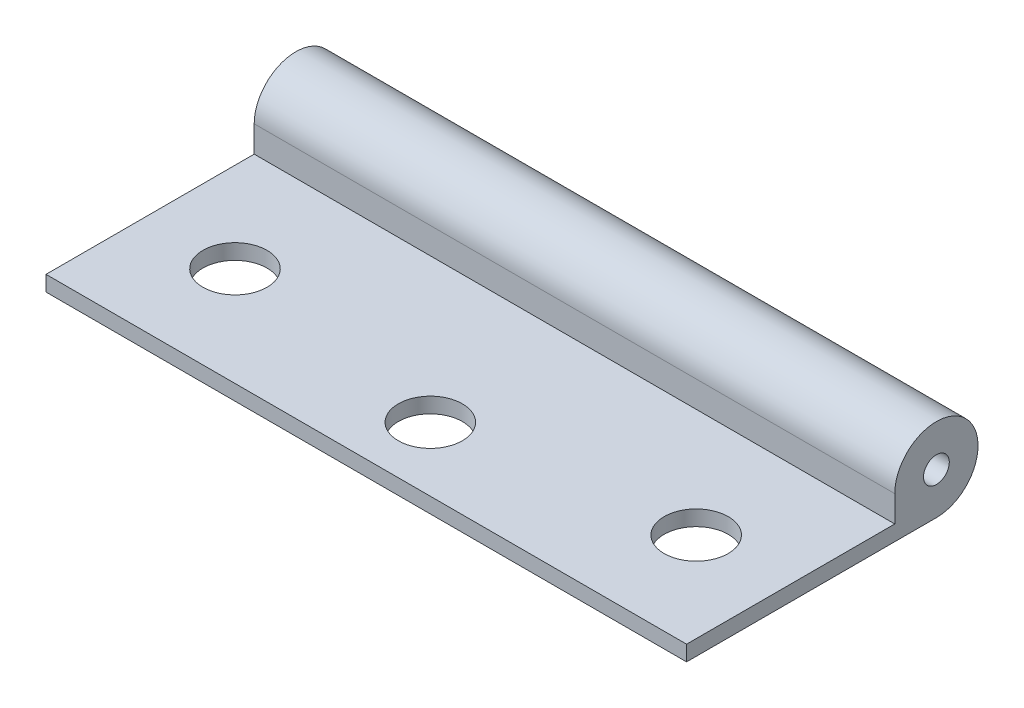
SolidWorks part; units mm, degrees
material "不锈钢 (铁素体)"
ref_plane "前视基准面" through (0, 0, 0) normal (0, 0, 1) x (1, 0, 0)
ref_plane "上视基准面" through (0, 0, 0) normal (0, 1, 0) x (1, 0, 0)
ref_plane "右视基准面" through (0, 0, 0) normal (1, 0, 0) x (0, 0, -1)
sketch "草图1" plane through (0, 0, 0) normal (0, 1, 0) x (1, 0, 0)
  line L0 (25, 0) -> (25, -16.25) construction
  line L1 (0, 0) -> (50, 0)
  line L2 (0, 0) -> (0, -16.25)
  line L3 (0, -16.25) -> (50, -16.25)
  line L4 (50, 0) -> (50, -16.25)
  line L5 (-4.5227, 3.25) -> (59.7314, 3.25) construction
  circle A0 centre (7, -8.5) radius 2.5
  circle A1 centre (43, -8.5) radius 2.5
  circle A2 centre (25, -11.25) radius 2.5
  dimension "D1" = 36
  dimension "D2" = 11.75
  dimension "D3" = 29
  dimension "D6" = 5
  dimension "D4" = 39
  dimension "D5" = 50
  dimension "D7" = 6.5
extrude "凸台-拉伸1" add sketch "草图1" along normal blind 1.2
sketch "草图2" plane through (0, 0, 0) normal (-1, 0, 0) x (0, 0, 1)
  line L0 (0, 0) -> (16.25, 0) construction
  line L1 (0, 1.2) -> (0, 0) construction
  line L2 (0, 0) -> (-3.25, 0)
  line L3 (0, 0) -> (0, 3.25)
  arc A0 (0, 3.25) -> (-3.25, 0) centre (-3.25, 3.25) ccw
  circle A1 centre (-3.25, 3.25) radius 1.0057
  dimension "D1" = 6.5
extrude "凸台-拉伸2" add sketch "草图2" against normal up to surface (50 mm away) up to face at (50, 0.6, 8.125)
